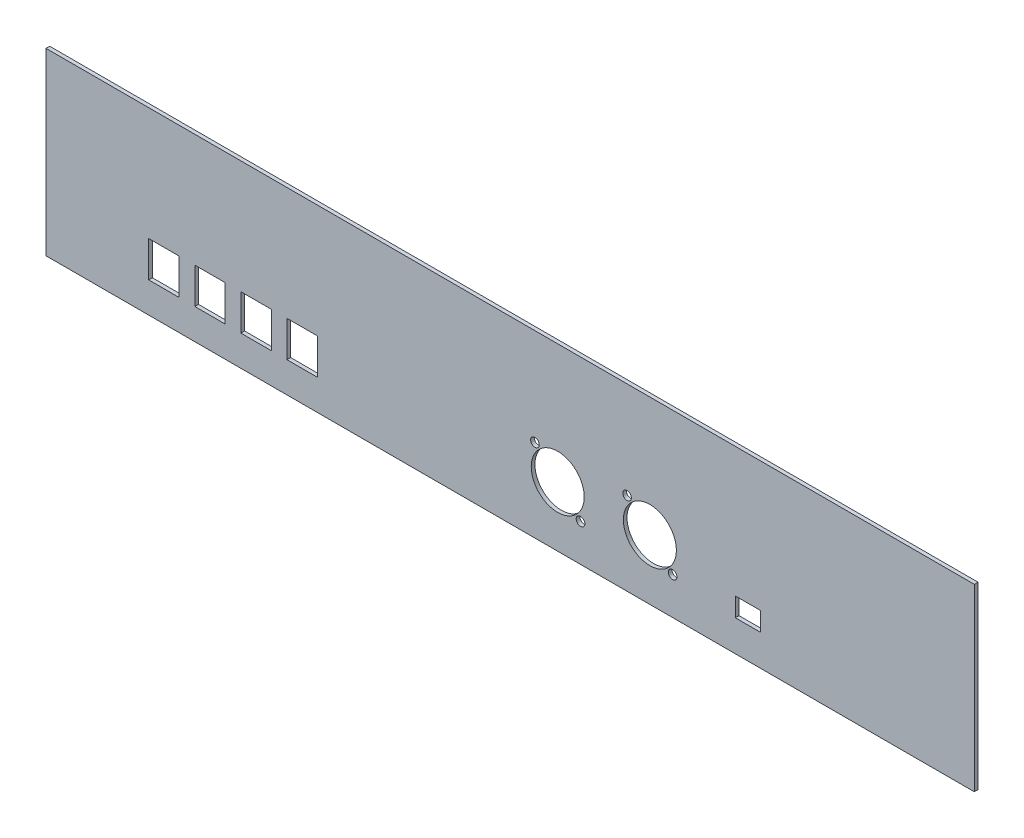
SolidWorks part; units mm, degrees
ref_plane "Front Plane" through (0, 0, 0) normal (0, 0, 1) x (1, 0, 0)
ref_plane "Top Plane" through (0, 0, 0) normal (0, 1, 0) x (1, 0, 0)
ref_plane "Right Plane" through (0, 0, 0) normal (1, 0, 0) x (0, 0, -1)
sketch "Panel" plane through (0, 0, 0) normal (0, 0, 1) x (1, 0, 0)
  line L1 (0, 0) -> (403, 0)
  line L2 (0, 0) -> (0, 78)
  line L3 (0, 78) -> (403, 78)
  line L4 (403, 0) -> (403, 78)
  dimension "D1" = 403
  dimension "D2" = 78
extrude "Boss-Extrude1" add sketch "Panel" along normal blind 1.6
sketch "XLR4" plane through (0, 0, 0) normal (0, 0, 1) x (1, 0, 0)
  circle A0 centre (222.15, 26.1) radius 11.5
  circle A1 centre (212.25, 36) radius 1.875
  circle A2 centre (232.05, 16.2) radius 1.875
  circle A3 centre (262.15, 26.1) radius 11.5
  circle A4 centre (252.25, 36) radius 1.875
  circle A5 centre (272.05, 16.2) radius 1.875
  point P6 (158.0408, 22.0901)
  point P15 (0, 0)
  dimension "D2" = 3.75
  dimension "D9" = 23
  dimension "D3" = 19.8
  dimension "D4" = 19.8
  dimension "D5" = 9.9
  dimension "D6" = 232.05
  dimension "D7" = 16.2
  dimension "D8" = 9.9
  dimension "D10" = 9.9
  dimension "D11" = 9.9
  dimension "D12" = 19.8
  dimension "D13" = 19.8
  dimension "D14" = 272.05
sketch "RJ11" plane through (0, 0, 0) normal (0, 0, 1) x (1, 0, 0)
  line L0 (64.6, 28.8) -> (77.8, 28.8)
  line L1 (44.6, 28.8) -> (57.8, 28.8)
  line L2 (44.6, 28.8) -> (44.6, 13.25)
  line L3 (44.6, 13.25) -> (57.8, 13.25)
  line L4 (57.8, 28.8) -> (57.8, 13.25)
  line L5 (64.6, 28.8) -> (64.6, 13.25)
  line L6 (64.6, 13.25) -> (77.8, 13.25)
  line L7 (77.8, 28.8) -> (77.8, 13.25)
  line L8 (84.6, 28.8) -> (97.8, 28.8)
  line L9 (84.6, 28.8) -> (84.6, 13.25)
  line L10 (84.6, 13.25) -> (97.8, 13.25)
  line L11 (97.8, 28.8) -> (97.8, 13.25)
  line L12 (104.6, 28.8) -> (117.8, 28.8)
  line L13 (104.6, 28.8) -> (104.6, 13.25)
  line L14 (104.6, 13.25) -> (117.8, 13.25)
  line L15 (117.8, 28.8) -> (117.8, 13.25)
  dimension "D1" = 13.2
  dimension "D2" = 15.55
  dimension "D3" = 44.6
  dimension "D4" = 13.25
  dimension "D6" = 6.8
  dimension "D5" = 4
extrude "Cut-Extrude2" cut sketch "XLR4" along normal up to surface (1.6 mm away) up to face at (201.5, 39, 1.6)
sketch "DC PORT" plane through (0, 0, 0) normal (0, 0, 1) x (1, 0, 0)
  line L1 (299.25, 21.75) -> (310.1, 21.75)
  line L2 (299.25, 21.75) -> (299.25, 13.55)
  line L3 (299.25, 13.55) -> (310.1, 13.55)
  line L4 (310.1, 21.75) -> (310.1, 13.55)
  dimension "D1" = 10.85
  dimension "D2" = 8.2
  dimension "D3" = 13.55
  dimension "D4" = 299.25
extrude "Cut-Extrude3" cut sketch "RJ11" along normal up to surface (1.6 mm away) up to face at (210.375, 36, 1.6)
extrude "Cut-Extrude4" cut sketch "DC PORT" along normal up to surface (1.6 mm away) up to face at (71.2, 21.025, 1.6)
equation "\"D5@XLR4\" = \"D3@XLR4\" / 2"
equation "\"D8@XLR4\" = \"D5@XLR4\""
